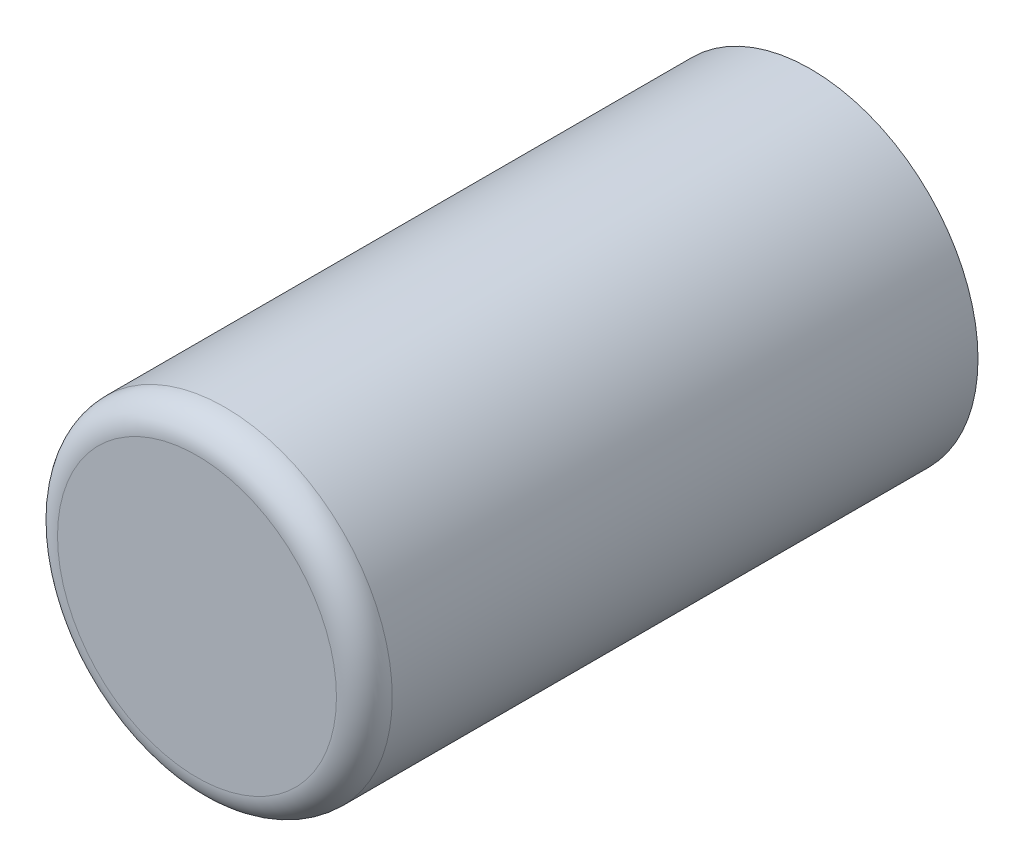
SolidWorks part; units mm, degrees
ref_plane "Front" through (0, 0, 0) normal (0, 0, 1) x (1, 0, 0)
ref_plane "Top" through (0, 0, 0) normal (0, 1, 0) x (1, 0, 0)
ref_plane "Right" through (0, 0, 0) normal (1, 0, 0) x (0, 0, -1)
other "Configuration Table"
sketch "Sketch1" plane through (0, 0, 0) normal (0, 0, 1) x (1, 0, 0)
  circle A0 centre (0, 0) radius 30
  dimension "D1" = 60
extrude "Boss-Extrude1" add sketch "Sketch1" along normal blind 110
fillet "Fillet1" radius 5 1 edges at (30, 0, 110)
shell "Shell1" thickness 1
